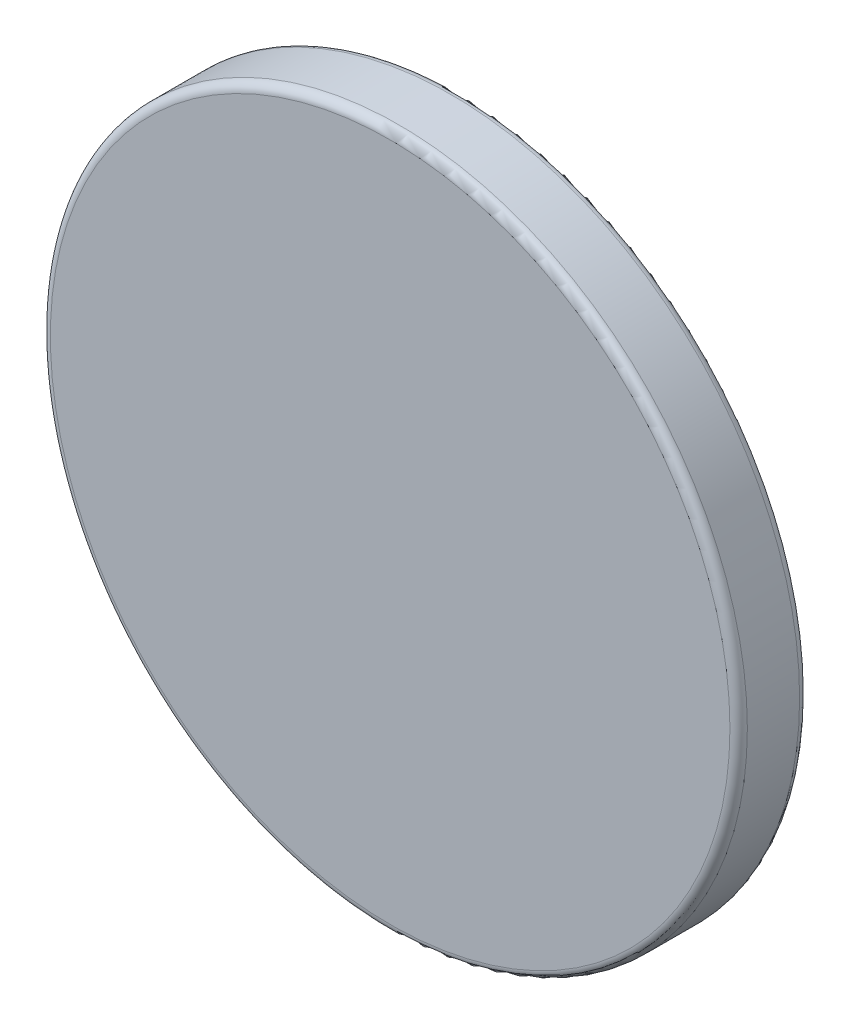
SolidWorks part; units mm, degrees
ref_plane "Plan de face" through (0, 0, 0) normal (0, 0, 1) x (1, 0, 0)
ref_plane "Plan de dessus" through (0, 0, 0) normal (0, 1, 0) x (1, 0, 0)
ref_plane "Plan de droite" through (0, 0, 0) normal (1, 0, 0) x (0, 0, -1)
sketch "Esquisse1" plane through (0, 0, 0) normal (0, 0, 1) x (1, 0, 0)
  circle A0 centre (0, 0) radius 10
  dimension "D1" = 20
extrude "Boss.-Extru.1" add sketch "Esquisse1" along normal blind 2
fillet "Congé1" radius 0.25 2 edges at (10, 0, 0) (10, 0, 2)
sketch "Esquisse2" plane through (0, 0, 0) normal (0, 0, -1) x (-1, 0, 0)
  line L0 (-5, -3.01) -> (5, -3.01) construction
  text T0 "S" font "Century Gothic" height 6
  point P4 (-9.75, 0)
  point P5 (-5.4037, 0)
  point P6 (0, -3.01)
  point P7 (7.1405, 0)
  dimension "D1" = 10
extrude "Enlèv. mat.-Extru.1" cut sketch "Esquisse2" against normal blind 0.25
